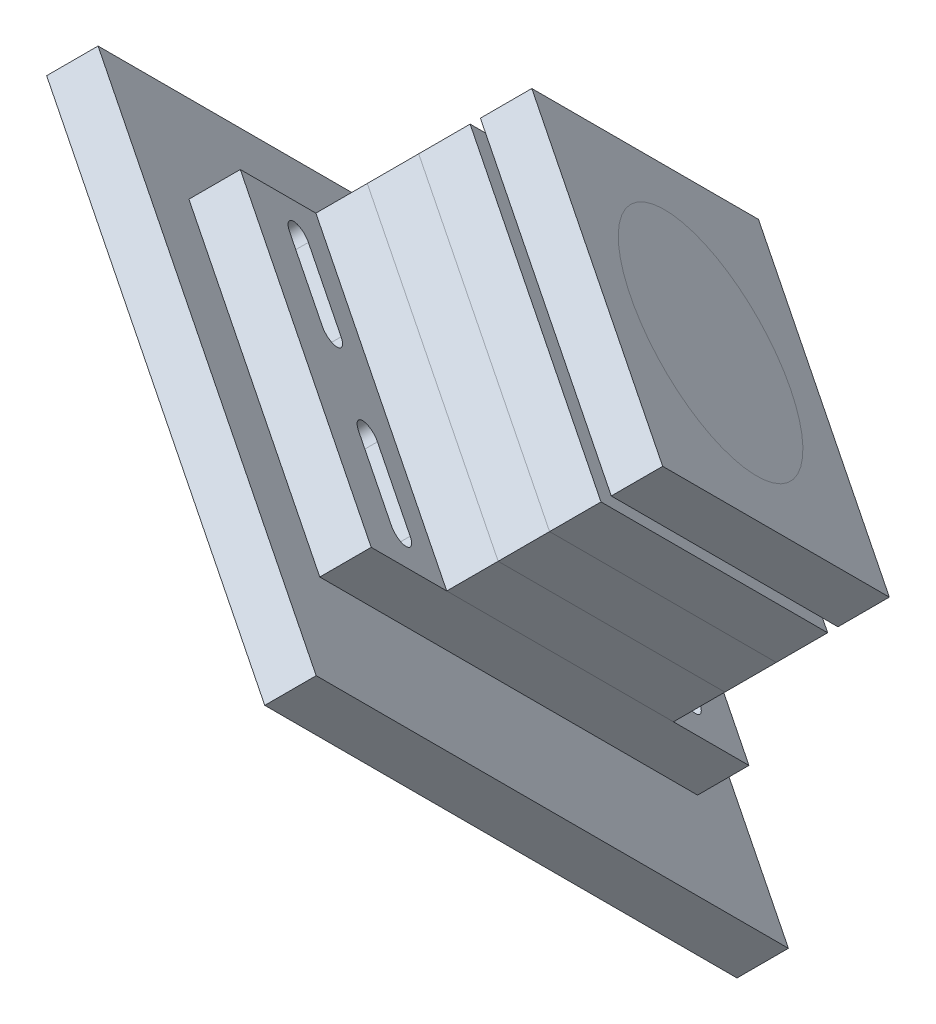
SolidWorks part; units mm, degrees
ref_plane "Front Plane" through (0, 0, 0) normal (0, 0, 1) x (1, 0, 0)
ref_plane "Top Plane" through (0, 0, 0) normal (0, 1, 0) x (1, 0, 0)
ref_plane "Right Plane" through (0, 0, 0) normal (1, 0, 0) x (0, 0, -1)
sketch "Sketch1" plane through (0, 0, 0) normal (0, 1, 0) x (1, 0, 0)
  line L1 (0, 0) -> (80, 0)
  line L2 (0, 0) -> (0, 80)
  line L3 (0, 80) -> (80, 80)
  line L4 (80, 0) -> (80, 80)
  dimension "D1" = 80
  dimension "D2" = 80
extrude "Boss-Extrude1" add sketch "Sketch1" along normal blind 80
sketch3d "3DSketch1"
  line L0 (0, 80, 0) -> (80, 0, 0)
  line L1 (80, 0, 0) -> (0, 0, -80)
  line L2 (0, 0, -80) -> (0, 80, 0)
ref_plane "Plane1" through (26.6667, 26.6667, -26.6667) normal (0.5774, 0.5774, -0.5774) x (-0.8165, 0.4082, -0.4082)
sketch "Sketch2" plane through (26.6667, 26.6667, -26.6667) normal (0.5774, 0.5774, -0.5774) x (-0.8165, 0.4082, -0.4082)
  circle A0 centre (0, 0) radius 97.9507
extrude "Cut-Extrude1" cut sketch "Sketch2" along normal through all
sketch "Sketch3" plane through (26.6667, 26.6667, -26.6667) normal (0.5774, 0.5774, -0.5774) x (-0.4082, -0.4082, -0.8165)
  circle A0 centre (0, 0) radius 12.7
  circle A1 centre (0, 0) radius 78.3026
  dimension "D1" = 25.4
extrude "Cut-Extrude2" cut sketch "Sketch3" against normal blind 40
ref_plane "Plane2" through (0, 0, 0) normal (0.5774, 0.5774, -0.5774) x (-0.8165, 0.4082, -0.4082)
ref_plane "Plane3" through (11.547, 11.547, -11.547) normal (0.5774, 0.5774, -0.5774) x (-0.8165, 0.4082, -0.4082)
sketch "Sketch4" plane through (11.547, 11.547, -11.547) normal (0.5774, 0.5774, -0.5774) x (-0.8165, 0.4082, -0.4082)
  circle A0 centre (0, 0) radius 14.1057
extrude "Cut-Extrude3" cut sketch "Sketch4" along normal blind 40
ref_plane "Plane4" through (8.0829, 8.0829, -8.0829) normal (0.5774, 0.5774, -0.5774) x (0.8165, -0.4082, 0.4082)
sketch "Sketch6" plane through (8.0829, 8.0829, -8.0829) normal (0.5774, 0.5774, -0.5774) x (0.8165, -0.4082, 0.4082)
  line L0 (11.8394, -4.5955) -> (-1.9399, -12.551)
  line L1 (11.8394, -4.5955) -> (-1.9399, -12.551)
  line L2 (11.8394, 4.5955) -> (-1.9399, 12.551)
  line L3 (11.8394, 4.5955) -> (-1.9399, 12.551)
  line L4 (-9.8995, -7.9555) -> (-9.8995, 7.9555)
  line L5 (-9.8995, -7.9555) -> (-9.8995, 7.9555)
  line L7 (18, -18) -> (-18, -18)
  line L8 (18, -18) -> (18, 18)
  line L9 (18, 18) -> (-18, 18)
  line L10 (-18, -18) -> (-18, 18)
  line L11 (18, -18) -> (-18, 18) construction
  line L12 (18, 18) -> (-18, -18) construction
  arc A0 (-9.8995, -7.9555) -> (-1.9399, -12.551) centre (0, 0) ccw
  arc A1 (11.8394, -4.5955) -> (11.8394, 4.5955) centre (0, 0) ccw
  arc A2 (-1.9399, 12.551) -> (-9.8995, 7.9555) centre (0, 0) ccw
  arc A3 (-1.9399, 12.551) -> (-9.8995, 7.9555) centre (0, 0) ccw
  arc A4 (11.8394, -4.5955) -> (11.8394, 4.5955) centre (0, 0) ccw
  arc A5 (-9.8995, -7.9555) -> (-1.9399, -12.551) centre (0, 0) ccw
  dimension "D1" = 36
  dimension "D2" = 36
extrude "Boss-Extrude2" add sketch "Sketch6" against normal blind 5 separate body
sketch "Sketch7" plane through (5.1962, 5.1962, -5.1962) normal (-0.5774, -0.5774, 0.5774) x (0.4082, 0.4082, 0.8165)
  line L0 (6.364, 10.9905) -> (6.364, -10.9905)
  line L1 (6.364, 10.9905) -> (6.364, -10.9905)
  line L2 (-12.7, 0.0161) -> (6.336, 11.0066)
  line L3 (-12.7, 0.0161) -> (6.336, 11.0066)
  line L4 (-12.7, -0.0161) -> (6.336, -11.0066)
  line L5 (-12.7, -0.0161) -> (6.336, -11.0066)
  line L10 (6.5885, 24.5885) -> (-24.5885, 6.5885)
  line L11 (-24.5885, 6.5885) -> (-6.5885, -24.5885)
  line L12 (-6.5885, -24.5885) -> (24.5885, -6.5885)
  line L13 (24.5885, -6.5885) -> (6.5885, 24.5885)
  line L14 (6.5885, 24.5885) -> (-24.5885, 6.5885)
  line L15 (-24.5885, 6.5885) -> (-6.5885, -24.5885)
  line L16 (-6.5885, -24.5885) -> (24.5885, -6.5885)
  line L17 (24.5885, -6.5885) -> (6.5885, 24.5885)
  arc A0 (6.336, -11.0066) -> (6.364, -10.9905) centre (0, 0) ccw
  arc A1 (6.364, 10.9905) -> (6.336, 11.0066) centre (0, 0) ccw
  arc A2 (-12.7, 0.0161) -> (-12.7, -0.0161) centre (0, 0) ccw
  arc A3 (-12.7, 0.0161) -> (-12.7, -0.0161) centre (0, 0) ccw
  arc A4 (6.364, 10.9905) -> (6.336, 11.0066) centre (0, 0) ccw
  arc A5 (6.336, -11.0066) -> (6.364, -10.9905) centre (0, 0) ccw
  dimension "D1" = 0
extrude "Boss-Extrude3" add sketch "Sketch7" along normal blind 5 separate body
sketch "Sketch8" plane through (2.3094, 2.3094, -2.3094) normal (-0.5774, -0.5774, 0.5774) x (0.4082, 0.4082, 0.8165)
  line L0 (-5.6569, 0) -> (2.8284, 4.899)
  line L1 (-5.6569, 0) -> (2.8284, 4.899)
  line L2 (2.8284, 4.899) -> (2.8284, -4.899)
  line L3 (2.8284, 4.899) -> (2.8284, -4.899)
  line L4 (-5.6569, 0) -> (2.8284, -4.899)
  line L5 (-5.6569, 0) -> (2.8284, -4.899)
  line L10 (24.5885, -6.5885) -> (6.5885, 24.5885)
  line L11 (6.5885, 24.5885) -> (-24.5885, 6.5885)
  line L12 (-24.5885, 6.5885) -> (-6.5885, -24.5885)
  line L13 (-6.5885, -24.5885) -> (24.5885, -6.5885)
  line L14 (24.5885, -6.5885) -> (6.5885, 24.5885)
  line L15 (6.5885, 24.5885) -> (-24.5885, 6.5885)
  line L16 (-24.5885, 6.5885) -> (-6.5885, -24.5885)
  line L17 (-6.5885, -24.5885) -> (24.5885, -6.5885)
  dimension "D1" = 0
extrude "Boss-Extrude4" add sketch "Sketch8" along normal blind 5 separate body
sketch "Sketch11" plane through (8.0829, 8.0829, -8.0829) normal (0.5774, 0.5774, -0.5774) x (0.8165, -0.4082, 0.4082)
  line L0 (0, 0) -> (0, -7.2839)
  line L1 (0, 0) -> (-4.4153, 0)
  circle A0 centre (-15, -15.3) radius 1.5
  circle A1 centre (15, -15.3) radius 1.5
  circle A2 centre (15, 15.3) radius 1.5
  circle A3 centre (-15, 15.3) radius 1.5
  dimension "D1" = 3
  dimension "D2" = 15
  dimension "D3" = 15.3
sketch "Sketch12" plane through (11.547, 11.547, -11.547) normal (0.5774, 0.5774, -0.5774) x (-0.4082, -0.4082, -0.8165)
  line L4 (24.5885, 6.5885) -> (-6.5885, 24.5885)
  line L5 (-6.5885, 24.5885) -> (-24.5885, -6.5885)
  line L6 (-24.5885, -6.5885) -> (6.5885, -24.5885)
  line L7 (6.5885, -24.5885) -> (24.5885, 6.5885)
  line L8 (24.5885, 6.5885) -> (-6.5885, 24.5885)
  line L9 (-6.5885, 24.5885) -> (-24.5885, -6.5885)
  line L10 (-24.5885, -6.5885) -> (6.5885, -24.5885)
  line L11 (6.5885, -24.5885) -> (24.5885, 6.5885)
  circle A0 centre (0, 0) radius 12.7
  dimension "D1" = 0
extrude "Boss-Extrude6" add sketch "Sketch12" against normal blind 5 separate body
ref_plane "Plane5" through (-0.5774, -0.5774, 0.5774) normal (-0.5774, -0.5774, 0.5774) x (-0.8165, 0.4082, -0.4082)
sketch "Sketch15" plane through (-0.5774, -0.5774, 0.5774) normal (-0.5774, -0.5774, 0.5774) x (-0.8165, 0.4082, -0.4082)
  line L0 (-14, 24.5) -> (-5, 24.5)
  line L1 (-18, -30) -> (18, -30)
  line L2 (-18, -30) -> (-18, 30)
  line L3 (-18, 30) -> (18, 30)
  line L4 (18, -30) -> (18, 30)
  line L5 (-18, -30) -> (18, 30) construction
  line L6 (-18, 30) -> (18, -30) construction
  line L7 (-14, 21.5) -> (-5, 21.5)
  line L10 (14, 24.5) -> (5, 24.5)
  line L11 (14, 21.5) -> (5, 21.5)
  line L12 (14, -24.5) -> (5, -24.5)
  line L13 (14, -21.5) -> (5, -21.5)
  line L14 (-14, -24.5) -> (-5, -24.5)
  line L15 (-14, -21.5) -> (-5, -21.5)
  arc A0 (-14, 24.5) -> (-14, 21.5) centre (-14, 23) ccw
  arc A1 (-5, 21.5) -> (-5, 24.5) centre (-5, 23) ccw
  arc A2 (14, 24.5) -> (14, 21.5) centre (14, 23) cw
  arc A3 (5, 21.5) -> (5, 24.5) centre (5, 23) cw
  arc A4 (14, -24.5) -> (14, -21.5) centre (14, -23) ccw
  arc A5 (5, -21.5) -> (5, -24.5) centre (5, -23) ccw
  arc A6 (-14, -24.5) -> (-14, -21.5) centre (-14, -23) cw
  arc A7 (-5, -21.5) -> (-5, -24.5) centre (-5, -23) cw
  point P0 (0, 0)
  dimension "D5" = 3
  dimension "D6" = 3
  dimension "D1" = 36
  dimension "D2" = 60
  dimension "D3" = 4
  dimension "D4" = 7
  dimension "D7" = 7
  dimension "D8" = 9
extrude "Boss-Extrude8" add sketch "Sketch15" along normal blind 5 separate body
ref_plane "Plane6" through (-3.4641, -3.4641, 3.4641) normal (-0.5774, -0.5774, 0.5774) x (-0.8165, 0.4082, -0.4082)
sketch "Sketch16" plane through (-3.4641, -3.4641, 3.4641) normal (-0.5774, -0.5774, 0.5774) x (-0.8165, 0.4082, -0.4082)
  line L1 (-30, 37.5) -> (30, 37.5)
  line L2 (-30, 37.5) -> (-30, -37.5)
  line L3 (-30, -37.5) -> (30, -37.5)
  line L4 (30, 37.5) -> (30, -37.5)
  line L5 (-30, 37.5) -> (30, -37.5) construction
  line L6 (-30, -37.5) -> (30, 37.5) construction
  line L10 (-11, 18.5) -> (-11, 27.5)
  line L11 (-8, 27.5) -> (-8, 18.5)
  line L12 (11, 18.5) -> (11, 27.5)
  line L13 (8, 27.5) -> (8, 18.5)
  line L14 (-11, -18.5) -> (-11, -27.5)
  line L15 (-8, -27.5) -> (-8, -18.5)
  line L16 (8, -27.5) -> (8, -18.5)
  line L17 (11, -18.5) -> (11, -27.5)
  arc A0 (-8, 27.5) -> (-11, 27.5) centre (-9.5, 27.5) ccw
  arc A1 (-11, 18.5) -> (-8, 18.5) centre (-9.5, 18.5) ccw
  arc A2 (8, 27.5) -> (11, 27.5) centre (9.5, 27.5) cw
  arc A3 (11, 18.5) -> (8, 18.5) centre (9.5, 18.5) cw
  arc A4 (-8, -27.5) -> (-11, -27.5) centre (-9.5, -27.5) cw
  arc A5 (-11, -18.5) -> (-8, -18.5) centre (-9.5, -18.5) cw
  arc A6 (11, -18.5) -> (8, -18.5) centre (9.5, -18.5) ccw
  arc A7 (8, -27.5) -> (11, -27.5) centre (9.5, -27.5) ccw
  point P0 (0, 0)
  dimension "D4" = 3
  dimension "D6" = 3
  dimension "D1" = 75
  dimension "D2" = 60
extrude "Boss-Extrude9" add sketch "Sketch16" along normal blind 5 separate body
sketch "Sketch18" plane through (24.4949, -12.2474, 12.2474) normal (0.8165, -0.4082, 0.4082) x (0.3651, -0.1826, -0.9129)
  line L0 (-32.8421, 19.0695) -> (25.2526, -28.3647)
  line L1 (-3.7947, -4.6476) -> (-6.957, -8.5206)
  line L2 (22.0904, -32.2376) -> (-36.0044, 15.1965) construction
  point P9 (-6.957, -8.5206)
  point P10 (-3.7947, -4.6476)
sketch "Sketch19" plane through (-6.3509, -6.3509, 6.3509) normal (-0.5774, -0.5774, 0.5774) x (0.4082, 0.4082, 0.8165)
  line L0 (0, 0) -> (15, -25.9808)
  line L1 (0, 0) -> (15, -25.9808)
  line L2 (0, 0) -> (6.3081, 3.642)
  line L3 (0, 0) -> (-2.2077, 3.8238)
  line L9 (-27.3779, -21.5801) -> (-32.3779, -12.9199)
  line L10 (-7.4593, -10.0801) -> (-12.4593, -1.4199)
  line L11 (-38.0477, 6.9006) -> (-33.0477, -1.7596)
  line L12 (-18.1292, 18.4006) -> (-13.1292, 9.7404)
  line L13 (-27.3779, -21.5801) -> (-23.0477, -19.0801)
  line L14 (-32.3779, -12.9199) -> (-28.0477, -10.4199)
  line L15 (-37.3779, -4.2596) -> (-33.0477, -1.7596)
  line L16 (-42.3779, 4.4006) -> (-38.0477, 6.9006)
  line L17 (-37.3779, -4.2596) -> (-42.3779, 4.4006)
  line L18 (-28.0477, -10.4199) -> (-23.0477, -19.0801)
  line L19 (-17.4593, 7.2404) -> (-22.4593, 15.9006)
  line L20 (-8.1292, 1.0801) -> (-3.1292, -7.5801)
  line L21 (-22.4593, 15.9006) -> (-18.1292, 18.4006)
  line L22 (-7.4593, -10.0801) -> (-3.1292, -7.5801)
  line L23 (-12.4593, -1.4199) -> (-8.1292, 1.0801)
  line L24 (17.3779, 38.9006) -> (13.0477, 36.4006)
  line L25 (13.0477, 36.4006) -> (18.0477, 27.7404)
  line L26 (22.3779, 30.2404) -> (17.3779, 38.9006)
  line L27 (22.3779, 30.2404) -> (18.0477, 27.7404)
  line L28 (27.3779, 21.5801) -> (23.0477, 19.0801)
  line L29 (32.3779, 12.9199) -> (27.3779, 21.5801)
  line L30 (23.0477, 19.0801) -> (28.0477, 10.4199)
  line L31 (32.3779, 12.9199) -> (28.0477, 10.4199)
  line L32 (12.4593, 1.4199) -> (8.1292, -1.0801)
  line L33 (12.4593, 1.4199) -> (7.4593, 10.0801)
  line L34 (3.1292, 7.5801) -> (8.1292, -1.0801)
  line L35 (7.4593, 10.0801) -> (3.1292, 7.5801)
  line L36 (2.4593, 18.7404) -> (-1.8708, 16.2404)
  line L37 (-2.5407, 27.4006) -> (-6.8708, 24.9006)
  line L38 (2.4593, 18.7404) -> (-2.5407, 27.4006)
  line L39 (-6.8708, 24.9006) -> (-1.8708, 16.2404)
  line L40 (-17.4593, 7.2404) -> (-13.1292, 9.7404)
  circle A0 centre (-20.7502, 5.3404) radius 1.5
  circle A1 centre (-5.7502, -20.6404) radius 1.5
  circle A2 centre (20.7502, -5.3404) radius 1.5
  circle A3 centre (5.7502, 20.6404) radius 1.5
  point P53 (-17.476, -44.7308)
  dimension "D1" = 30
  dimension "D2" = 30
  dimension "D5" = 5
  dimension "D6" = 5
  dimension "D8" = 10
